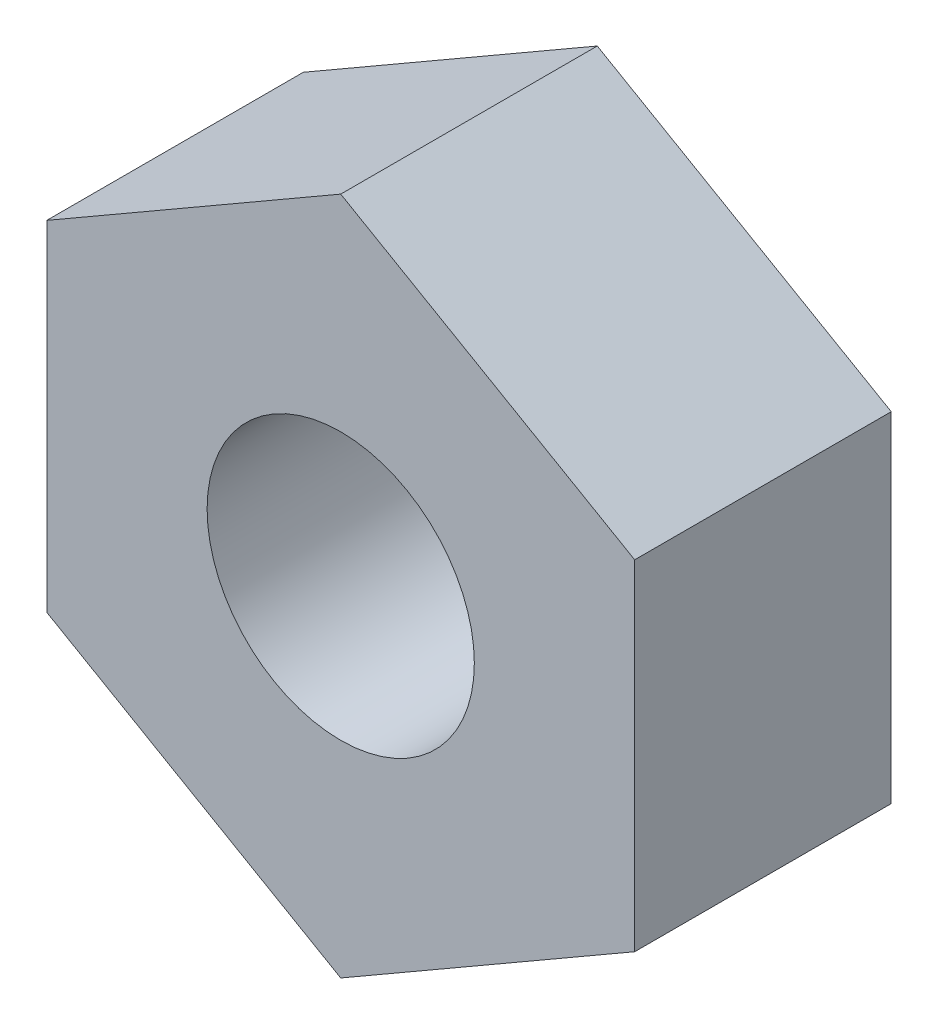
SolidWorks part; units mm, degrees
ref_plane "前视基准面" through (0, 0, 0) normal (0, 0, 1) x (1, 0, 0)
ref_plane "上视基准面" through (0, 0, 0) normal (0, 1, 0) x (1, 0, 0)
ref_plane "右视基准面" through (0, 0, 0) normal (1, 0, 0) x (0, 0, -1)
other "Configuration Table"
sketch "Profile_1" plane through (0, 0, 0) normal (0, 0, 1) x (1, 0, 0)
  line L0 (2.75, 1.5877) -> (0, 3.1754)
  line L1 (0, 3.1754) -> (-2.75, 1.5877)
  line L2 (-2.75, 1.5877) -> (-2.75, -1.5877)
  line L3 (-2.75, -1.5877) -> (0, -3.1754)
  line L4 (0, -3.1754) -> (2.75, -1.5877)
  line L5 (2.75, -1.5877) -> (2.75, 1.5877)
  circle A0 centre (0, 0) radius 1.25
extrude "Hex_nut" add sketch "Profile_1" along normal blind 2.4 from offset 0
